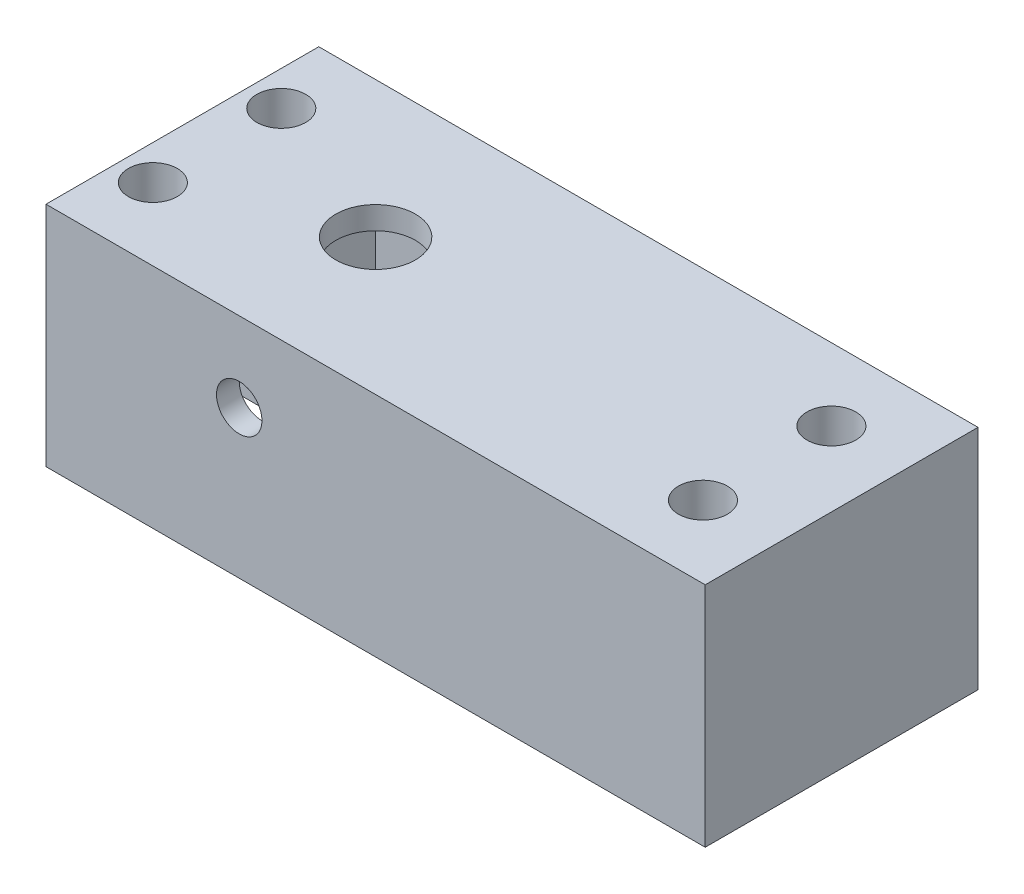
SolidWorks part; units mm, degrees
material "Cast Alloy Steel"
ref_plane "Front Plane" through (0, 0, 0) normal (0, 0, 1) x (1, 0, 0)
ref_plane "Top Plane" through (0, 0, 0) normal (0, 1, 0) x (1, 0, 0)
ref_plane "Right Plane" through (0, 0, 0) normal (1, 0, 0) x (0, 0, -1)
sketch "Sketch1" plane through (0, 0, 0) normal (0, 1, 0) x (1, 0, 0)
  line L1 (-34.3486, 0) -> (20.6514, 0)
  line L2 (-34.3486, 0) -> (-34.3486, 20)
  line L3 (-34.3486, 20) -> (20.6514, 20)
  line L4 (20.6514, 0) -> (20.6514, 20)
extrude "Boss-Extrude1" add sketch "Sketch1" along normal blind 7
sketch "Sketch4" plane through (0, 7, 0) normal (0, 1, 0) x (1, 0, 0)
  line L0 (-34.3486, 10) -> (-17.3486, 10)
  line L1 (-34.3486, 20) -> (-34.3486, 0) construction
  circle A0 centre (-17.3486, 10) radius 2.5
extrude "Cut-Extrude3" cut sketch "Sketch4" against normal blind 1 contours A0
sketch "Sketch5" plane through (0, 6, 0) normal (0, 1, 0) x (1, 0, 0)
  circle A0 centre (-17.3486, 10) radius 1.5
extrude "Cut-Extrude4" cut sketch "Sketch5" against normal through all
sketch "Sketch6" plane through (0, 0, 0) normal (0, -1, 0) x (-1, 0, 0)
  line L0 (-20.6514, 20) -> (34.3486, 20) construction
  line L1 (34.3486, 0) -> (27.3486, 0)
  line L2 (34.3486, 0) -> (34.3486, 20)
  line L3 (34.3486, 20) -> (27.3486, 20)
  line L4 (27.3486, 0) -> (27.3486, 20)
  line L5 (34.3486, 0) -> (-20.6514, 0) construction
  line L6 (-20.6514, 20) -> (-13.6514, 20)
  line L7 (-20.6514, 20) -> (-20.6514, 0)
  line L8 (-20.6514, 0) -> (-13.6514, 0)
  line L9 (-13.6514, 20) -> (-13.6514, 0)
extrude "Boss-Extrude2" add sketch "Sketch6" along normal blind 18
sketch "Sketch7" plane through (0, -18, 0) normal (0, -1, 0) x (-1, 0, 0)
  circle A0 centre (31.2986, 15.65) radius 2.15
  circle A1 centre (0, 0) radius 1
  circle A2 centre (31.2986, 4.35) radius 2.15
sketch "Sketch9" plane through (0, -18, 0) normal (0, -1, 0) x (-1, 0, 0)
extrude "Cut-Extrude5" cut sketch "Sketch7" against normal blind 7
sketch "Sketch11" plane through (0, -18, 0) normal (0, -1, 0) x (-1, 0, 0)
  circle A0 centre (-17.1014, 15.65) radius 2.15
  circle A2 centre (-17.1014, 4.35) radius 2.15
extrude "Cut-Extrude6" cut sketch "Sketch11" against normal blind 7
sketch "Sketch12" plane through (0, 0, 0) normal (0, 0, 1) x (1, 0, 0)
  line L1 (20.6514, -18) -> (-34.3486, -18)
  line L2 (20.6514, -18) -> (20.6514, 7)
  line L3 (20.6514, 7) -> (-34.3486, 7)
  line L4 (-34.3486, -18) -> (-34.3486, 7)
extrude "Boss-Extrude3" add sketch "Sketch12" along normal blind 2
sketch "Sketch13" plane through (0, 0, -20) normal (0, 0, -1) x (-1, 0, 0)
  line L1 (34.3486, -18) -> (-20.6514, -18)
  line L2 (34.3486, -18) -> (34.3486, 7)
  line L3 (34.3486, 7) -> (-20.6514, 7)
  line L4 (-20.6514, -18) -> (-20.6514, 7)
extrude "Boss-Extrude4" add sketch "Sketch13" along normal blind 2
sketch "Sketch14" plane through (0, 0, 2) normal (0, 0, 1) x (1, 0, 0)
  line L0 (20.6514, -5.5) -> (-34.3486, -5.5)
  line L1 (20.6514, -18) -> (20.6514, 7) construction
  line L2 (-34.3486, 7) -> (-34.3486, -18) construction
  circle A0 centre (-6.8486, -5.5) radius 3
extrude "Cut-Extrude7" [suppressed] cut sketch "Sketch14" against normal through all contours L0 A0 | L0 A0
sketch "Sketch15" plane through (20.6514, 0, 0) normal (1, 0, 0) x (0, 0, -1)
  line L4 (22, 7) -> (-2, 7)
  line L5 (-2, 7) -> (-2, -18)
  line L6 (-2, -18) -> (22, -18)
  line L7 (22, -18) -> (22, 7)
  line L8 (22, 7) -> (-2, 7)
  line L9 (-2, 7) -> (-2, -18)
  line L10 (-2, -18) -> (22, -18)
  line L11 (22, -18) -> (22, 7)
  dimension "D1" = 0
extrude "Boss-Extrude5" add sketch "Sketch15" along normal blind 10
sketch "Sketch16" plane through (30.6514, 0, 0) normal (1, 0, 0) x (0, 0, -1)
  line L2 (22, -18) -> (18.5373, -14.3931)
  line L3 (-2, 7) -> (1.4627, 3.3931)
  line L4 (-2, -18) -> (1.4627, -14.3931)
  line L5 (22, 7) -> (18.5373, 3.3931)
  circle A0 centre (1.4627, -14.3931) radius 2
  circle A1 centre (18.5373, -14.3931) radius 2
  circle A2 centre (1.4627, 3.3931) radius 2
  circle A3 centre (18.5373, 3.3931) radius 2
extrude "Cut-Extrude8" [suppressed] cut sketch "Sketch16" against normal up to surface (17 mm away)
sketch "Sketch18" plane through (0, 7, 0) normal (0, 1, 0) x (1, 0, 0)
  line L0 (-34.3486, -2) -> (-5.3486, -2)
  line L1 (-5.3486, -2) -> (-5.3486, 22)
  line L4 (-34.3486, 22) -> (-34.3486, -2)
  line L5 (-34.3486, -2) -> (30.6514, -2)
  line L6 (30.6514, -2) -> (30.6514, 22)
  line L7 (30.6514, 22) -> (-34.3486, 22)
  line L8 (-34.3486, 22) -> (-34.3486, -2)
  line L10 (30.6514, -2) -> (30.6514, 22)
  line L11 (30.6514, 22) -> (-34.3486, 22)
  circle M6 centre (-17.3486, 10) radius 2.5
  line M7 (-34.3486, 22) -> (-34.3486, -2)
  line M8 (-34.3486, -2) -> (30.6514, -2)
  line M10 (30.6514, 22) -> (-34.3486, 22)
  dimension "D1" = 0
extrude "Cut-Extrude10" [suppressed] cut sketch "Sketch18" against normal blind 1 contours L1 M8 M10 M7 M6
sketch "Sketch19" [suppressed] plane through (0, 6, 0) normal (0, 1, 0) x (1, 0, 0)
  circle A0 centre (-17.3486, 10) radius 10
  circle A1 centre (-17.3486, 10) radius 8
extrude "Cut-Extrude11" [suppressed] cut sketch "Sketch19" against normal blind 2
sketch "Sketch22" [suppressed] plane through (0, 6, 0) normal (0, 1, 0) x (1, 0, 0)
  circle A1 centre (-17.3486, 10) radius 8
  circle A2 centre (-17.3486, 10) radius 8
  dimension "D1" = 0
extrude "Cut-Extrude12" [suppressed] cut sketch "Sketch22" against normal blind 1
sketch "Sketch23" [suppressed] plane through (0, 6, 0) normal (0, 1, 0) x (1, 0, 0)
  line L0 (-34.3486, 22) -> (-30.3486, 22)
  line L1 (-30.3486, 22) -> (-30.3486, -2)
  line L4 (-34.3486, -2) -> (-5.3486, -2)
  line L5 (-5.3486, -2) -> (-5.3486, 22)
  line L6 (-5.3486, 22) -> (-34.3486, 22)
  line L7 (-34.3486, 22) -> (-34.3486, -2)
  line L8 (-34.3486, -2) -> (-5.3486, -2)
  line L9 (-5.3486, -2) -> (-5.3486, 22)
  line L11 (-34.3486, 22) -> (-34.3486, -2)
  line M7 (-34.3486, -2) -> (-5.3486, -2)
  line M9 (-5.3486, 22) -> (-34.3486, 22)
  line M10 (-34.3486, 22) -> (-34.3486, -2)
  dimension "D1" = 0
extrude "Cut-Extrude13" [suppressed] cut sketch "Sketch23" against normal blind 3 contours L1 M9 M10 M7
fillet "Fillet1" [suppressed] radius 2
sketch "Sketch24" [suppressed] plane through (-5.3486, 0, 0) normal (-1, 0, 0) x (0, 0, 1)
  line L4 (2, 7) -> (-22, 7)
  line L5 (-22, 7) -> (-22, 6)
  line L6 (-22, 6) -> (2, 6)
  line L7 (2, 6) -> (2, 7)
  line L8 (2, 7) -> (-22, 7)
  line L9 (-22, 7) -> (-22, 6)
  line L10 (-22, 6) -> (2, 6)
  line L11 (2, 6) -> (2, 7)
  dimension "D1" = 0
extrude "Cut-Extrude16" [suppressed] cut sketch "Sketch24" against normal blind 5
sketch "Sketch26" [suppressed] plane through (0, 6, 0) normal (0, 1, 0) x (1, 0, 0)
  line L0 (-5.3486, -2) -> (-4.3486, -2)
  line L1 (-4.3486, -2) -> (-4.3486, 22)
  line L2 (-4.3486, 22) -> (-5.3486, 22)
  line L4 (-5.3486, 22) -> (-34.3486, 22)
  line L5 (-34.3486, 22) -> (-34.3486, -2)
  line L6 (-34.3486, -2) -> (-5.3486, -2)
  line L7 (-34.3486, 22) -> (-34.3486, -2)
  line L8 (-5.3486, 22) -> (-34.3486, 22)
  line L9 (-5.3486, -2) -> (-5.3486, 22)
  line L10 (-34.3486, -2) -> (-5.3486, -2)
  line L11 (-5.3486, -2) -> (-5.3486, 22)
  dimension "D1" = 0
extrude "Cut-Extrude17" [suppressed] cut sketch "Sketch26" against normal blind 3
fillet "Fillet4" [suppressed] radius 2
fillet "Fillet5" [suppressed] radius 2
sketch "Sketch27" [suppressed] plane through (0, 3, 0) normal (0, 1, 0) x (1, 0, 0)
  line L0 (-32.3486, -2) -> (-32.3486, 4)
  line L1 (-2.3486, -2) -> (-2.3486, 4)
  line L2 (-32.3486, 22) -> (-32.3486, 16)
  line L3 (-2.3486, 22) -> (-2.3486, 16)
  line L4 (-30.3486, -2) -> (-30.3486, 22)
  line L5 (-30.3486, 22) -> (-34.3486, 22)
  line L6 (-34.3486, 22) -> (-34.3486, -2)
  line L7 (-34.3486, -2) -> (-30.3486, -2)
  line L8 (-30.3486, -2) -> (-30.3486, 22)
  line L9 (-30.3486, 22) -> (-34.3486, 22)
  line L10 (-34.3486, 22) -> (-34.3486, -2)
  line L11 (-34.3486, -2) -> (-30.3486, -2)
  line L12 (-4.3486, 22) -> (-4.3486, -2)
  line L13 (-4.3486, -2) -> (-0.3486, -2)
  line L14 (-0.3486, -2) -> (-0.3486, 22)
  line L15 (-0.3486, 22) -> (-4.3486, 22)
  line L16 (-4.3486, 22) -> (-4.3486, -2)
  line L17 (-4.3486, -2) -> (-0.3486, -2)
  line L18 (-0.3486, -2) -> (-0.3486, 22)
  line L19 (-0.3486, 22) -> (-4.3486, 22)
  circle A0 centre (-32.3486, 16) radius 1
  circle A1 centre (-32.3486, 4) radius 1
  circle A2 centre (-2.3486, 16) radius 1
  circle A3 centre (-2.3486, 4) radius 1
  dimension "D1" = 0
  dimension "D2" = 0
extrude "Cut-Extrude18" [suppressed] cut sketch "Sketch27" against normal up to surface (3 mm away)
sketch "Sketch28" [suppressed] plane through (0, 0, 0) normal (0, 1, 0) x (1, 0, 0)
  circle A0 centre (-32.3486, 16) radius 1 construction
  circle A1 centre (-32.3486, 4) radius 1 construction
  circle A2 centre (-32.3486, 16) radius 1
  circle A3 centre (-32.3486, 4) radius 1
extrude "Cut-Extrude19" [suppressed] cut sketch "Sketch28" against normal blind 3
sketch "Sketch29" plane through (0, 7, 0) normal (0, 1, 0) x (1, 0, 0)
  line L4 (-34.3486, 22) -> (-34.3486, -2)
  line L5 (-34.3486, -2) -> (30.6514, -2)
  line L6 (30.6514, -2) -> (30.6514, 22)
  line L7 (30.6514, 22) -> (-34.3486, 22)
  line L8 (-34.3486, 22) -> (-34.3486, -2)
  line L9 (-34.3486, -2) -> (30.6514, -2)
  line L10 (30.6514, -2) -> (30.6514, 22)
  line L11 (30.6514, 22) -> (-34.3486, 22)
  dimension "D1" = 0
extrude "Cut-Extrude20" cut sketch "Sketch29" against normal blind 5
sketch "Sketch30" plane through (0, 0, 0) normal (0, 0, -1) x (-1, 0, 0)
  line L0 (27.3486, 0) -> (27.3486, -5)
  line L1 (27.3486, -18) -> (27.3486, 0) construction
  line L2 (27.3486, -5) -> (17.3486, -5)
  circle A0 centre (17.3486, -5) radius 2
extrude "Cut-Extrude21" cut sketch "Sketch30" against normal through all both and the other way through all
sketch "Sketch31" plane through (0, 0, 0) normal (0, -1, 0) x (1, 0, 0)
  circle A0 centre (-17.3486, -10) radius 3.5
extrude "Cut-Extrude22" cut sketch "Sketch31" against normal through all
sketch "Sketch32" plane through (30.6514, 0, 0) normal (1, 0, 0) x (0, 0, -1)
  line L4 (22, -18) -> (22, 2)
  line L5 (22, 2) -> (-2, 2)
  line L6 (-2, 2) -> (-2, -18)
  line L7 (-2, -18) -> (22, -18)
  line L8 (22, -18) -> (22, 2)
  line L9 (22, 2) -> (-2, 2)
  line L10 (-2, 2) -> (-2, -18)
  line L11 (-2, -18) -> (22, -18)
  dimension "D1" = 0
extrude "Cut-Extrude23" cut sketch "Sketch32" against normal blind 7
sketch "Sketch33" plane through (0, -11, 0) normal (0, -1, 0) x (1, 0, 0)
  circle A0 centre (17.1014, -15.65) radius 2.15 construction
  circle A1 centre (17.1014, -4.35) radius 2.15 construction
  circle A2 centre (-31.2986, -15.65) radius 2.15 construction
  circle A3 centre (-31.2986, -4.35) radius 2.15 construction
  circle A4 centre (17.1014, -15.65) radius 2.15
  circle A5 centre (17.1014, -4.35) radius 2.15
  circle A6 centre (-31.2986, -15.65) radius 2.15
  circle A7 centre (-31.2986, -4.35) radius 2.15
extrude "Cut-Extrude24" cut sketch "Sketch33" against normal through all
sketch "Sketch34" plane through (0, -18, 0) normal (0, -1, 0) x (1, 0, 0)
  line L0 (13.6514, -10) -> (23.6514, -10)
  line L1 (13.6514, 0) -> (13.6514, -20) construction
  line L2 (23.6514, -10) -> (23.6514, -9.841)
  line L3 (23.6514, -9.841) -> (23.6514, -11.841)
  line L4 (-34.3486, -22) -> (23.6514, -22)
  line L5 (23.6514, -22) -> (23.6514, 2)
  line L6 (23.6514, 2) -> (-34.3486, 2)
  line L7 (-34.3486, 2) -> (-34.3486, -22)
  line L8 (-34.3486, -22) -> (23.6514, -22)
  line L9 (23.6514, -22) -> (23.6514, 2)
  line L10 (23.6514, 2) -> (-34.3486, 2)
  line L11 (-34.3486, 2) -> (-34.3486, -22)
  line L12 (23.6514, -11.841) -> (13.6514, -11.841)
  line L13 (13.6514, -11.841) -> (13.6514, -7.841)
  line L14 (13.6514, -7.841) -> (23.6514, -7.841)
  dimension "D1" = 0
sketch "Sketch35" plane through (0, -18, 0) normal (0, -1, 0) x (1, 0, 0)
  line L0 (-27.3486, -10) -> (-34.3486, -10)
  line L1 (-27.3486, -20) -> (-27.3486, 0) construction
  line L2 (-34.3486, -10) -> (-34.3486, -12)
  line L3 (-34.3486, -12) -> (-27.3486, -12)
  line L4 (-34.3486, -22) -> (23.6514, -22)
  line L5 (23.6514, -22) -> (23.6514, 2)
  line L6 (23.6514, 2) -> (-34.3486, 2)
  line L7 (-34.3486, 2) -> (-34.3486, -22)
  line L8 (-34.3486, -22) -> (23.6514, -22)
  line L9 (23.6514, -22) -> (23.6514, 2)
  line L10 (23.6514, 2) -> (-34.3486, 2)
  line L11 (-34.3486, 2) -> (-34.3486, -22)
  line L12 (-27.3486, -12) -> (-27.3486, -10)
  line L13 (-27.3486, -10) -> (-27.3486, -8)
  line L14 (-27.3486, -8) -> (-34.3486, -8)
  line L15 (-34.3486, -8) -> (-34.3486, -10)
  line M9 (-27.3486, -20) -> (-27.3486, 0)
  line M16 (-34.3486, 2) -> (-34.3486, -22)
  dimension "D1" = 0
extrude "Cut-Extrude26" cut sketch "Sketch35" against normal offset from surface (17 mm away) 1 contours L14 L11 L0 M9 | L3 L0 M16 M9 up to face at (-17.3486, 0, -13.5)
